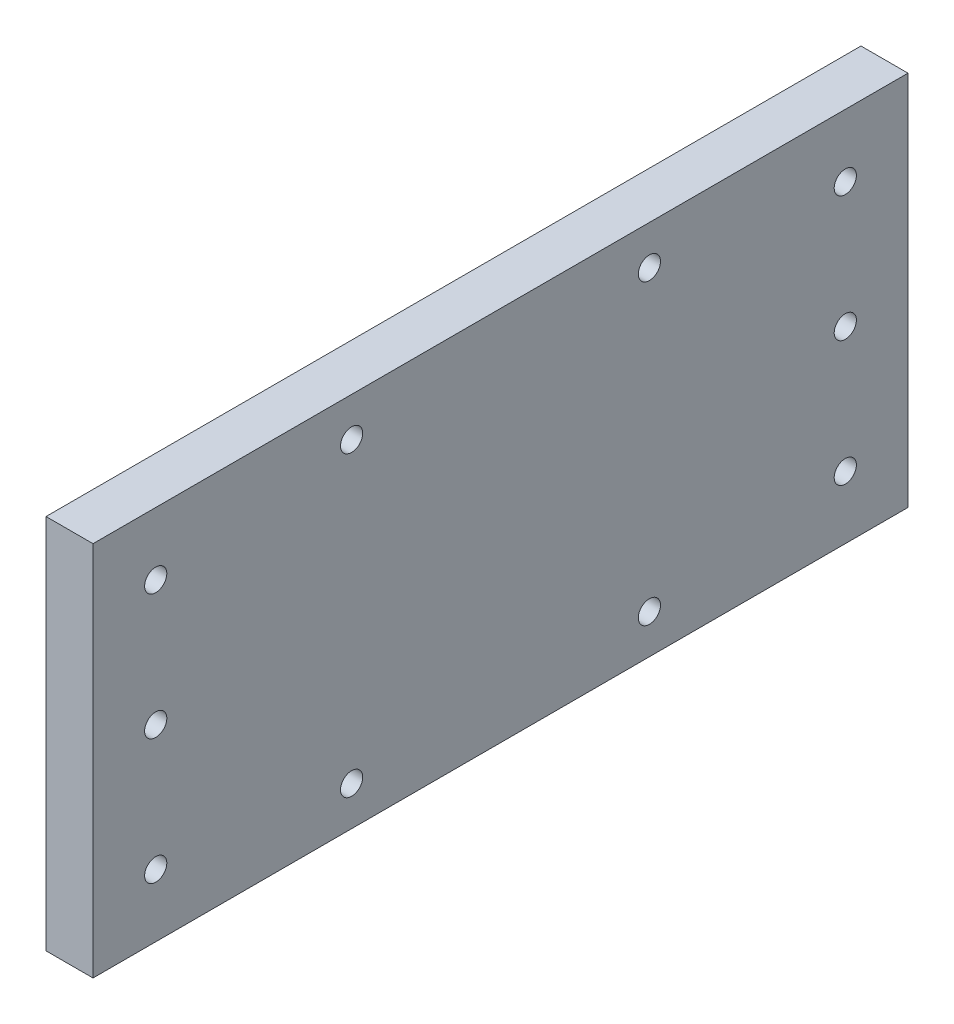
SolidWorks part; units mm, degrees
material "Plain Carbon Steel"
ref_plane "Front Plane" through (0, 0, 0) normal (0, 0, 1) x (1, 0, 0)
ref_plane "Top Plane" through (0, 0, 0) normal (0, 1, 0) x (1, 0, 0)
ref_plane "Right Plane" through (0, 0, 0) normal (1, 0, 0) x (0, 0, -1)
sketch "Sketch1" plane through (0, 0, 0) normal (0, 0, 1) x (1, 0, 0)
  line L1 (-4.7625, 38.1) -> (4.7625, 38.1)
  line L2 (-4.7625, 38.1) -> (-4.7625, -38.1)
  line L3 (-4.7625, -38.1) -> (4.7625, -38.1)
  line L4 (4.7625, 38.1) -> (4.7625, -38.1)
  line L5 (-4.7625, 38.1) -> (4.7625, -38.1) construction
  line L6 (-4.7625, -38.1) -> (4.7625, 38.1) construction
  point P0 (0, 0)
  dimension "D1" = 9.525
  dimension "D2" = 76.2
extrude "Boss-Extrude1" add sketch "Sketch1" along normal blind 165.1
hole_wizard "#8 Clearance Hole1" positions "Sketch3" profile "Sketch2" hole size "#8" standard "ANSI Inch" end condition through all
sketch "Sketch3" plane through (4.7625, 0, 0) normal (1, 0, 0) x (0, 0, -1)
  line L1 (-112.7125, 30.1625) -> (-52.3875, 30.1625)
  line L2 (-112.7125, 30.1625) -> (-112.7125, -30.1625)
  line L3 (-112.7125, -30.1625) -> (-52.3875, -30.1625)
  line L4 (-52.3875, 30.1625) -> (-52.3875, -30.1625)
  line L5 (-112.7125, 30.1625) -> (-52.3875, -30.1625) construction
  line L6 (-112.7125, -30.1625) -> (-52.3875, 30.1625) construction
  line L7 (0, 0) -> (-82.55, 0) construction
  line L9 (-82.55, 38.1) -> (-82.55, 0) construction
  line L10 (-165.1, 38.1) -> (0, 38.1) construction
  point P2 (-52.3875, -30.1625)
  point P55 (-112.7125, 30.1625)
  point P56 (-112.7125, -30.1625)
  point P57 (-52.3875, 30.1625)
  dimension "D1" = 60.325
  dimension "D2" = 60.325
sketch "Sketch2" plane through (4.7625, -30.1625, 52.3875) normal (0, 1, 0) x (0, 0, -1)
  line L0 (0, 0) -> (0, 9.525)
  line L1 (0, 9.525) -> (2.2479, 9.525)
  line L2 (2.2479, 9.525) -> (2.2479, 0)
  line L5 (2.2479, 0) -> (0, 0)
  line L11 (0, -6.35) -> (0, 107.95) construction
  dimension "Thru Hole Dia." = 4.4958
  dimension "Thru Hole Depth" = 9.525
hole_wizard "#8 Clearance Hole2" positions "Sketch5" profile "Sketch4" hole size "#8" standard "ANSI Inch" end condition through all
sketch "Sketch5" plane through (4.7625, 0, 0) normal (1, 0, 0) x (0, 0, -1)
  line L0 (-165.1, -38.1) -> (-165.1, 38.1) construction
  line L1 (-165.1, -38.1) -> (0, -38.1) construction
  line L2 (0, -38.1) -> (0, 38.1) construction
  point P0 (-152.4, 25.4)
  point P2 (-152.4, 0)
  point P4 (-152.4, -25.4)
  point P6 (-12.7, 25.4)
  point P8 (-12.7, 0)
  point P10 (-12.7, -25.4)
  dimension "D1" = 12.7
  dimension "D2" = 25.4
  dimension "D3" = 25.4
  dimension "D4" = 12.7
  dimension "D5" = 12.7
sketch "Sketch4" plane through (4.7625, 25.4, 152.4) normal (0, 1, 0) x (0, 0, -1)
  line L0 (0, 0) -> (0, 9.525)
  line L1 (0, 9.525) -> (2.2479, 9.525)
  line L2 (2.2479, 9.525) -> (2.2479, 0)
  line L5 (2.2479, 0) -> (0, 0)
  line L11 (0, -6.35) -> (0, 107.95) construction
  dimension "Thru Hole Dia." = 4.4958
  dimension "Thru Hole Depth" = 9.525
